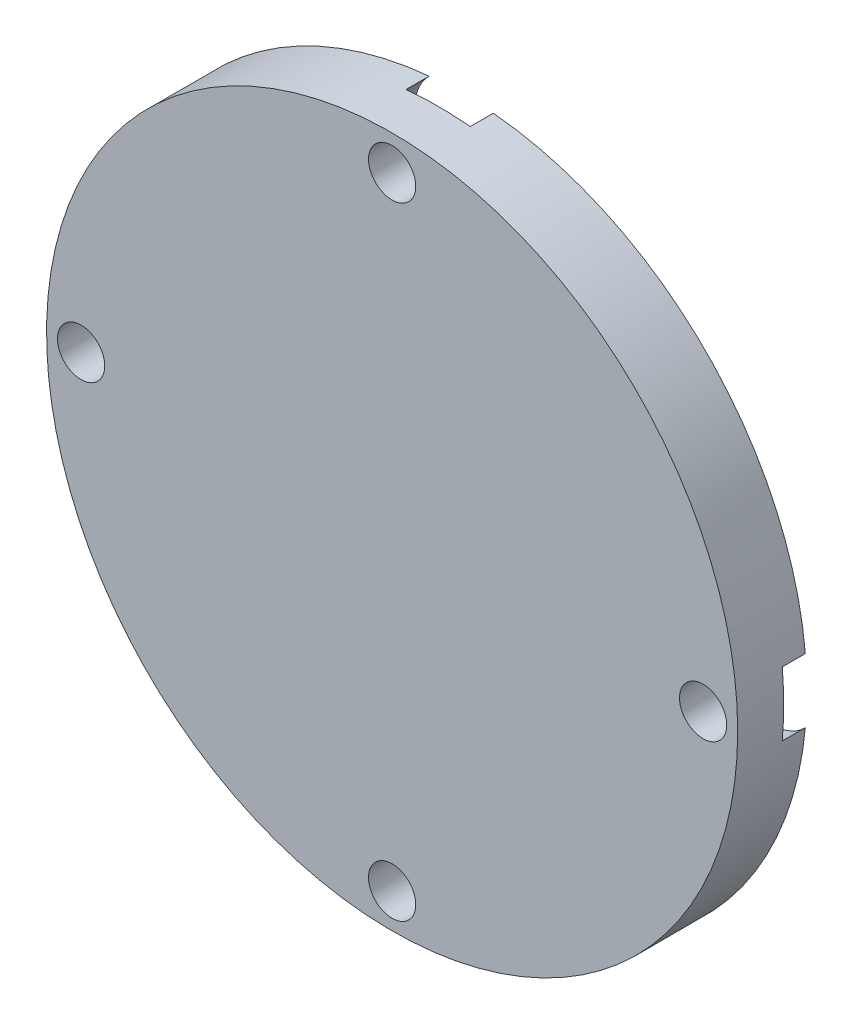
SolidWorks part; units mm, degrees
ref_plane "前视基准面" through (0, 0, 0) normal (0, 0, 1) x (1, 0, 0)
ref_plane "上视基准面" through (0, 0, 0) normal (0, 1, 0) x (1, 0, 0)
ref_plane "右视基准面" through (0, 0, 0) normal (1, 0, 0) x (0, 0, -1)
other "Configuration Table"
sketch "草图1" plane through (0, 0, 0) normal (0, 0, 1) x (1, 0, 0)
  circle A0 centre (0, 0) radius 15
  circle A1 centre (0, 0) radius 11.8687
extrude "凸台-拉伸1" add sketch "草图1" along normal blind 3
sketch "草图2" plane through (0, 0, 0) normal (0, 0, 1) x (1, 0, 0)
  line L0 (0, 0) -> (-13.5, 0)
  line L1 (0, 0) -> (0, 13.5)
  line L2 (0, 0) -> (13.5, 0)
  line L3 (0, 0) -> (0, -13.5)
  circle A0 centre (0, 13.5) radius 1.025
  circle A1 centre (13.5, 0) radius 1.025
  circle A2 centre (0, -13.5) radius 1.025
  circle A3 centre (-13.5, 0) radius 1.025
  point P16 (0, 0)
  dimension "D1" = 4
extrude "切除-拉伸2" cut sketch "草图2" along normal through all
sketch "草图3" plane through (0, 0, 0) normal (0, 0, -1) x (-1, 0, 0)
  circle A0 centre (0, 13.5) radius 2
  circle A1 centre (13.5, 0) radius 2
  circle A2 centre (-13.5, 0) radius 2
  circle A3 centre (0, -13.5) radius 2
extrude "切除-拉伸3" cut sketch "草图3" against normal blind 1
